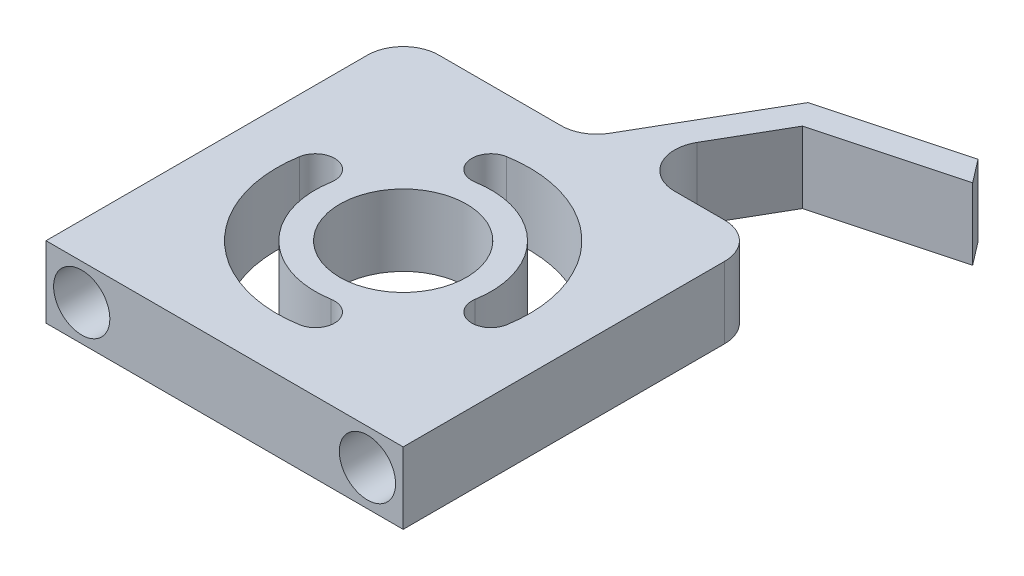
SolidWorks part; units mm, degrees
ref_plane "Front Plane" through (0, 0, 0) normal (0, 0, 1) x (1, 0, 0)
ref_plane "Top Plane" through (0, 0, 0) normal (0, 1, 0) x (1, 0, 0)
ref_plane "Right Plane" through (0, 0, 0) normal (1, 0, 0) x (0, 0, -1)
sketch "Sketch1" plane through (0, 0, 0) normal (0, 1, 0) x (1, 0, 0)
  line L0 (-1.3555, -1.4843) -> (23072.6219, 25264.6975) construction
  line L1 (-20, -20) -> (20, -20)
  line L2 (-20, -20) -> (-20, 20)
  line L3 (-20, 20) -> (20, 20)
  line L4 (20, -20) -> (20, 20)
  line L5 (0, 20) -> (0, -20) construction
  line L6 (-20, 0) -> (20, 0) construction
  line L7 (6804.3054, -1813.4769) -> (29890.5801, 23466.1705) construction
  line L8 (6796.5897, -1804.2862) -> (29882.8644, 23475.3612) construction
  line L9 (11.8322, -2) -> (11.8322, 0) construction
  line L10 (-2, 11.8322) -> (0, 11.8322) construction
  line L11 (-20, 20) -> (35335.3391, -35335.3391) construction
  arc A0 (-2, 11.8322) -> (11.8322, -2) centre (0, 0) cw construction
  circle A1 centre (-8.0922, -8.861) radius 2.15 construction
  circle A2 centre (8.0922, 8.861) radius 2.15 construction
  arc A3 (-11.8322, 2) -> (2, -11.8322) centre (0, 0) ccw construction
  arc A4 (-1.6417, 9.7122) -> (9.7122, -1.6417) centre (0, 0) cw
  arc A5 (-13.9521, 2.3583) -> (2.3583, -13.9521) centre (0, 0) ccw
  arc A6 (-2.3583, 13.9521) -> (13.9521, -2.3583) centre (0, 0) cw
  arc A7 (-9.7122, 1.6417) -> (1.6417, -9.7122) centre (0, 0) ccw
  arc A8 (-13.9521, 2.3583) -> (-9.7122, 1.6417) centre (-11.8322, 2) cw
  arc A9 (1.6417, -9.7122) -> (2.3583, -13.9521) centre (2, -11.8322) cw
  arc A10 (13.9521, -2.3583) -> (9.7122, -1.6417) centre (11.8322, -2) cw
  arc A11 (-1.6417, 9.7122) -> (-2.3583, 13.9521) centre (-2, 11.8322) cw
  circle A12 centre (0, 0) radius 7.1
  point P0 (0, 0)
  dimension "D5" = 4.3
  dimension "D6" = 4.3
  dimension "D1" = 40
  dimension "D7" = 12
  dimension "D9" = 2
extrude "Boss-Extrude1" add sketch "Sketch1" along normal blind 8
fillet "Fillet1" radius 4 2 edges at (20, 4, -20) (-20, 4, -20)
sketch "Sketch2" plane through (0, 0, 20) normal (0, 0, 1) x (1, 0, 0)
  line L0 (-20, 0) -> (20, 0) construction
  line L2 (20, 8) -> (20, 0) construction
  circle A0 centre (-16, 4) radius 3.15
  circle A1 centre (16, 4) radius 3.15
  dimension "D5" = 6.3
  dimension "D6" = 6.3
  dimension "D1" = 4
  dimension "D2" = 4
  dimension "D3" = 32
  dimension "D4" = 4
extrude "Cut-Extrude1" cut sketch "Sketch2" against normal blind 4.7
sketch "Sketch3" plane through (0, 8, 0) normal (0, 1, 0) x (1, 0, 0)
  line L0 (0, 20) -> (9.2669, 36.0508)
  line L1 (16, 20) -> (-16, 20) construction
  line L2 (9.2669, 36.0508) -> (24.296, 40.0778)
  line L3 (24.296, 40.0778) -> (26.2727, 37.5017)
  line L4 (26.2727, 37.5017) -> (11.2437, 33.4747)
  line L5 (11.2437, 33.4747) -> (3.4641, 20)
  line L6 (0, 20) -> (3.4641, 20)
  line L7 (20, -20) -> (20, 16) construction
  point P5 (21.172, 39.2664)
  point P9 (9.5682, 33.0278)
  point P10 (27.0363, 47.2518)
  point P13 (32.672, 42.6683)
  point P14 (30.8482, 45.1055)
  point P15 (24.296, 40.0778)
  dimension "D1" = 135
  dimension "D2" = 3
  dimension "D3" = 3
  dimension "D4" = 60
  dimension "D5" = 20
extrude "Boss-Extrude2" add sketch "Sketch3" against normal blind 8
fillet "Fillet2" radius 4 2 edges at (3.4641, 4, -20) (0, 4, -20)
equation "\"radcurve\"= 12mm"
equation "\"D7@Sketch1\"=\"radcurve\""
equation "\"hole\"= 4.3mm"
equation "\"middle\"= 4mm"
